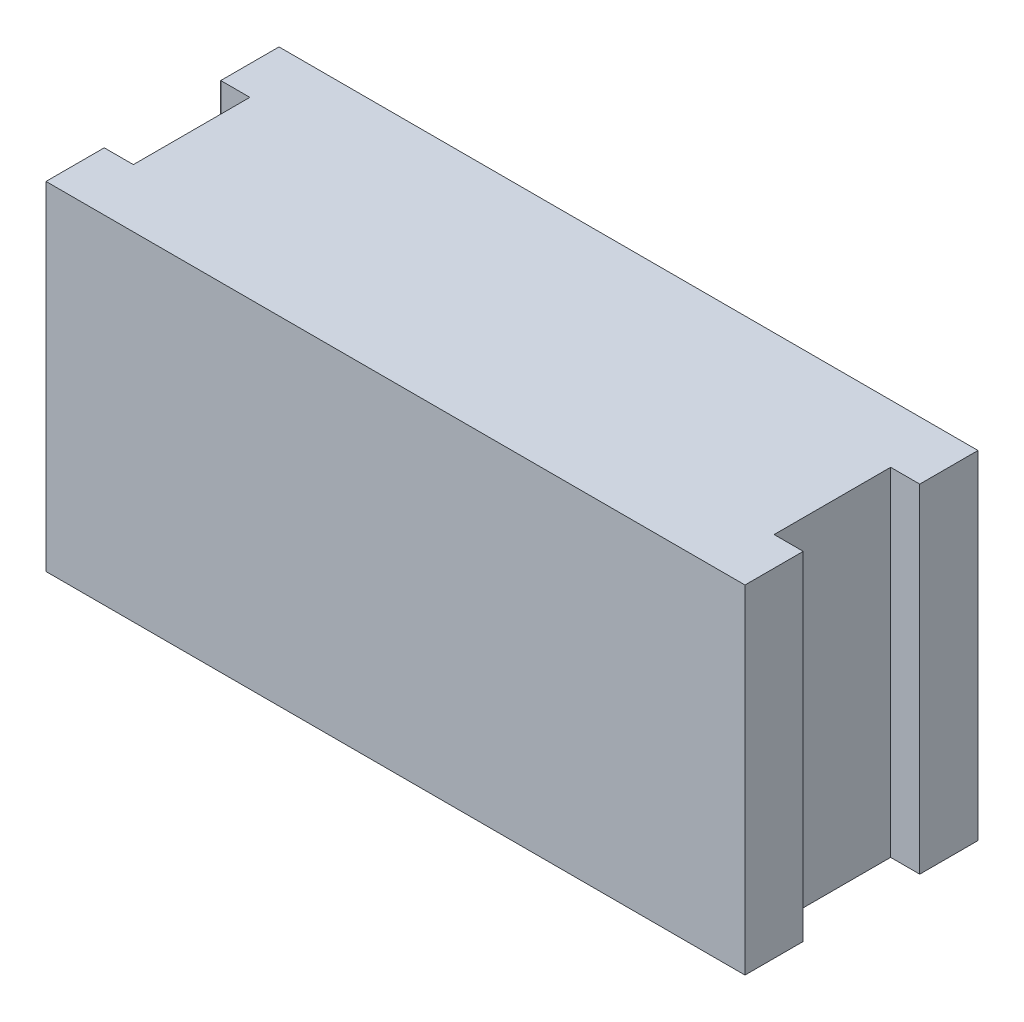
SolidWorks part; units mm, degrees
material "Бетон М200"
ref_plane "Спереди" through (0, 0, 0) normal (0, 0, 1) x (1, 0, 0)
ref_plane "Сверху" through (0, 0, 0) normal (0, 1, 0) x (1, 0, 0)
ref_plane "Справа" through (0, 0, 0) normal (1, 0, 0) x (0, 0, -1)
sketch "Эскиз1" plane through (0, 0, 0) normal (0, 1, 0) x (1, 0, 0)
  line L0 (0, -5639.6184) -> (0, 276341.2993) construction
  line L1 (-5639.6184, 0) -> (276341.2993, 0) construction
  line L2 (-600, 200) -> (600, 200)
  line L3 (600, 200) -> (600, 100)
  line L4 (-600, 200) -> (-600, 100)
  line L5 (600, 100) -> (550, 100)
  line L6 (-600, 100) -> (-550, 100)
  line L7 (550, 100) -> (550, -100)
  line L8 (-550, 100) -> (-550, -100)
  line L9 (550, -100) -> (600, -100)
  line L10 (-550, -100) -> (-600, -100)
  line L11 (600, -100) -> (600, -200)
  line L12 (-600, -100) -> (-600, -200)
  line L13 (600, 100) -> (600, 0) construction
  line L14 (650, 50) -> (550, 50) construction
  line L15 (-600, -200) -> (600, -200)
  point P8 (0, 200)
  point P16 (550, 0)
  point P20 (600, 50)
  point P23 (0, -200)
  point P24 (600, 50)
  dimension "D1" = 400
  dimension "D2" = 1200
extrude "Бобышка-Вытянуть1" add sketch "Эскиз1" along normal blind 580
